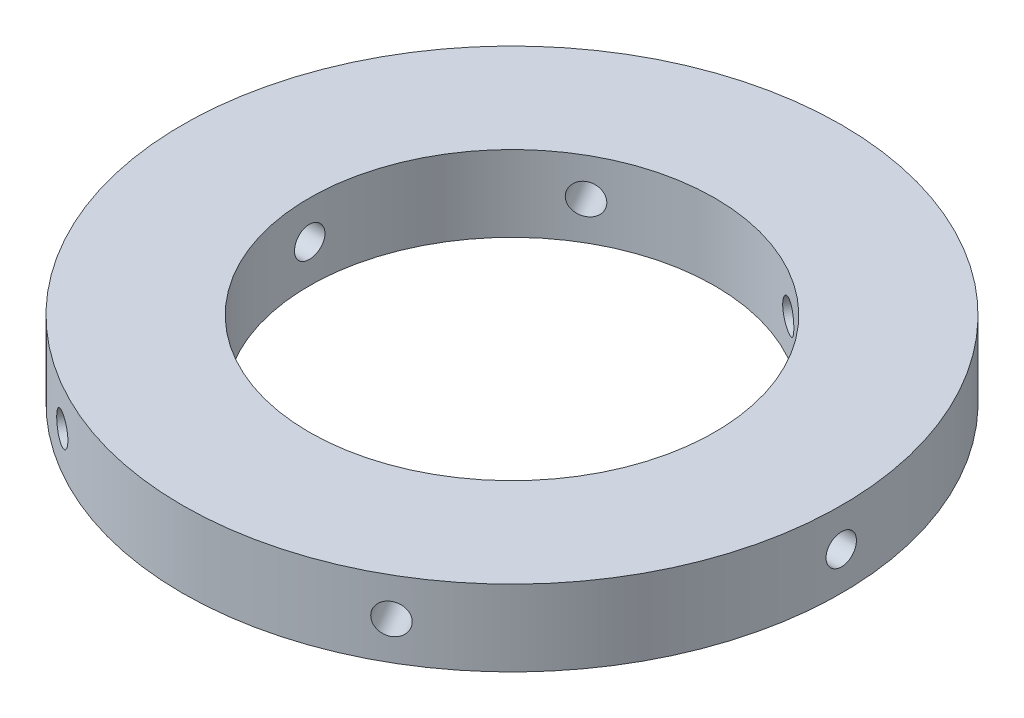
SolidWorks part; units mm, degrees
ref_plane "Front Plane" through (0, 0, 0) normal (0, 0, 1) x (1, 0, 0)
ref_plane "Top Plane" through (0, 0, 0) normal (0, 1, 0) x (1, 0, 0)
ref_plane "Right Plane" through (0, 0, 0) normal (1, 0, 0) x (0, 0, -1)
sketch "Sketch1" plane through (0, 0, 0) normal (0, 1, 0) x (1, 0, 0)
  line L0 (0, 0) -> (0, 87.698) construction
  line L1 (0, 0) -> (-128.1213, 0) construction
  circle A0 centre (0, 0) radius 65
  circle A1 centre (0, 0) radius 40
  point P2 (0, 0)
  point P5 (0, 0)
  dimension "D1" = 130
  dimension "D2" = 80
extrude "Boss-Extrude1" add sketch "Sketch1" along normal blind 15
sketch "Sketch2" plane through (0, 0, 0) normal (1, 0, 0) x (0, 0, -1)
  line L0 (65, 7.5) -> (-65, 7.5) construction
  line L1 (65, 0) -> (65, 15) construction
  line L2 (-65, 15) -> (-65, 0) construction
  circle A0 centre (0, 7.5) radius 3
  dimension "D1" = 6
extrude "Cut-Extrude1" cut sketch "Sketch2" against normal through all
pattern_circular "CirPattern1" count 6 over 360 about axis through (0, 15, 0) along (0, 1, 0) of "Cut-Extrude1"
equation "\"holes\"=6"
equation "\"D1@CirPattern1\"=\"holes\""
